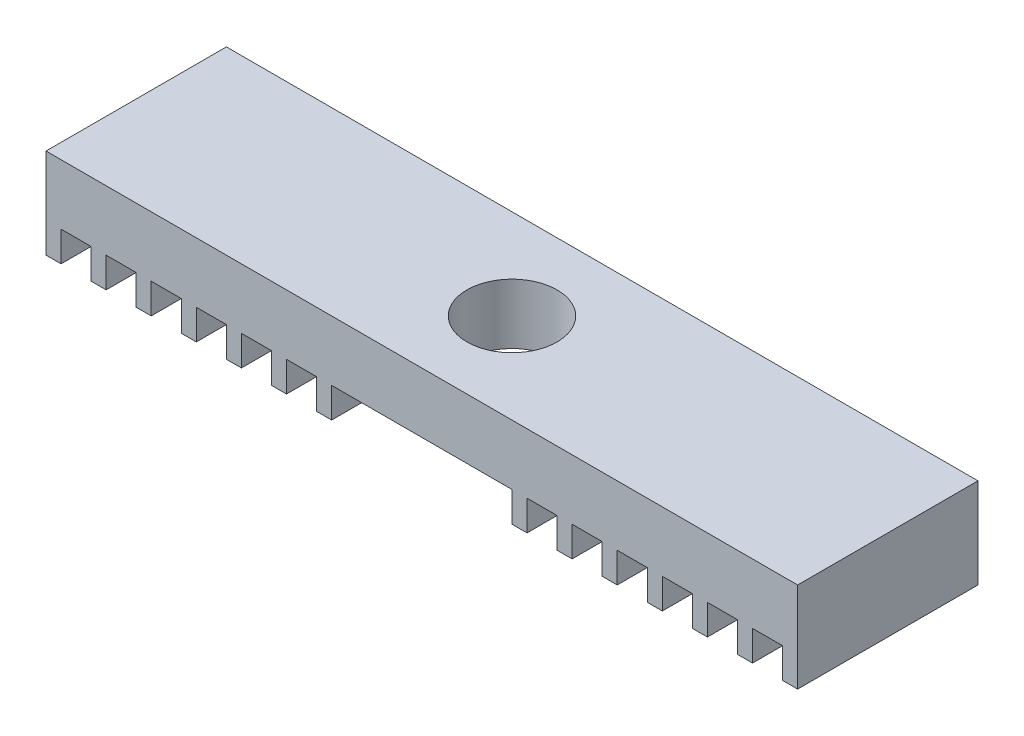
SolidWorks part; units mm, degrees
ref_plane "Front" through (0, 0, 0) normal (0, 0, 1) x (1, 0, 0)
ref_plane "Top" through (0, 0, 0) normal (0, 1, 0) x (1, 0, 0)
ref_plane "Right" through (0, 0, 0) normal (1, 0, 0) x (0, 0, -1)
sketch "Sketch1" plane through (0, 0, 0) normal (0, 0, 1) x (1, 0, 0)
  line L0 (17.4625, -1.5875) -> (17.4625, -3.175)
  line L1 (-19.8438, 1.5875) -> (19.8438, 1.5875)
  line L2 (-19.8438, 1.5875) -> (-19.8437, -1.5875)
  line L3 (-19.8437, -1.5875) -> (19.8438, -1.5875)
  line L4 (19.8438, 1.5875) -> (19.8438, -1.5875)
  line L5 (-19.8438, 1.5875) -> (19.8438, -1.5875) construction
  line L6 (-19.8437, -1.5875) -> (19.8438, 1.5875) construction
  line L8 (19.8438, -1.5875) -> (19.8438, -3.175)
  line L9 (19.8438, -3.175) -> (19.05, -3.175)
  line L10 (19.05, -1.5875) -> (19.05, -3.175)
  line L12 (16.6688, -1.5875) -> (16.6688, -3.175)
  line L13 (17.4625, -3.175) -> (16.6688, -3.175)
  line L14 (15.0813, -1.5875) -> (15.0813, -3.175)
  line L16 (14.2875, -1.5875) -> (14.2875, -3.175)
  line L17 (15.0813, -3.175) -> (14.2875, -3.175)
  line L18 (12.7, -1.5875) -> (12.7, -3.175)
  line L20 (11.9063, -1.5875) -> (11.9063, -3.175)
  line L21 (12.7, -3.175) -> (11.9063, -3.175)
  line L22 (10.3188, -1.5875) -> (10.3188, -3.175)
  line L24 (9.525, -1.5875) -> (9.525, -3.175)
  line L25 (10.3188, -3.175) -> (9.525, -3.175)
  line L26 (7.9375, -1.5875) -> (7.9375, -3.175)
  line L28 (7.1438, -1.5875) -> (7.1438, -3.175)
  line L29 (7.9375, -3.175) -> (7.1438, -3.175)
  line L30 (5.5563, -1.5875) -> (5.5563, -3.175)
  line L32 (4.7625, -1.5875) -> (4.7625, -3.175)
  line L33 (5.5563, -3.175) -> (4.7625, -3.175)
  line L34 (0, -15.8624) -> (0, 15.8624) construction
  line L35 (-19.8438, -3.175) -> (-19.05, -3.175)
  line L36 (-19.05, -1.5875) -> (-19.05, -3.175)
  line L38 (-19.8437, -1.5875) -> (-19.8438, -3.175)
  line L40 (-16.6688, -1.5875) -> (-16.6688, -3.175)
  line L41 (-17.4625, -3.175) -> (-16.6688, -3.175)
  line L42 (-17.4625, -1.5875) -> (-17.4625, -3.175)
  line L44 (-14.2875, -1.5875) -> (-14.2875, -3.175)
  line L45 (-15.0813, -3.175) -> (-14.2875, -3.175)
  line L46 (-15.0813, -1.5875) -> (-15.0813, -3.175)
  line L48 (-11.9063, -1.5875) -> (-11.9063, -3.175)
  line L49 (-12.7, -3.175) -> (-11.9063, -3.175)
  line L50 (-12.7, -1.5875) -> (-12.7, -3.175)
  line L52 (-9.525, -1.5875) -> (-9.525, -3.175)
  line L53 (-10.3188, -3.175) -> (-9.525, -3.175)
  line L54 (-10.3188, -1.5875) -> (-10.3188, -3.175)
  line L56 (-7.1438, -1.5875) -> (-7.1438, -3.175)
  line L57 (-7.9375, -3.175) -> (-7.1438, -3.175)
  line L58 (-7.9375, -1.5875) -> (-7.9375, -3.175)
  line L60 (-4.7625, -1.5875) -> (-4.7625, -3.175)
  line L61 (-5.5563, -3.175) -> (-4.7625, -3.175)
  line L62 (-5.5563, -1.5875) -> (-5.5563, -3.175)
  point P0 (0, 0)
  dimension "D1" = 39.6875
  dimension "D2" = 3.175
  dimension "D3" = 0.7937
  dimension "D4" = 1.5875
  dimension "D5" = 7
extrude "Boss-Extrude1" add sketch "Sketch1" along normal blind 9.525 contours L3 L38 L35 L36 | L3 L42 L41 L40 | L3 L46 L45 L44 | L3 L50 L49 L48 | L3 L54 L53 L52 | L3 L58 L57 L56 | L3 L62 L61 L60 | L33 L30 L3 L32 | L29 L26 L3 L28 | L25 L22 L3 L24 | L21 L18 L3 L20 | L17 L14 L3 L16 | L13 L0 L3 L12 | L3 L10 L9 L8 | L4 L1 L2 L3
sketch "Sketch2" plane through (0, 1.5875, 0) normal (0, 1, 0) x (1, 0, 0)
  line L0 (0, -2.6194) -> (0, 2.6194) construction
  circle A0 centre (0, -4.7625) radius 2.3813
  dimension "D1" = 4.7625
extrude "Cut-Extrude1" cut sketch "Sketch2" against normal blind 9.525
